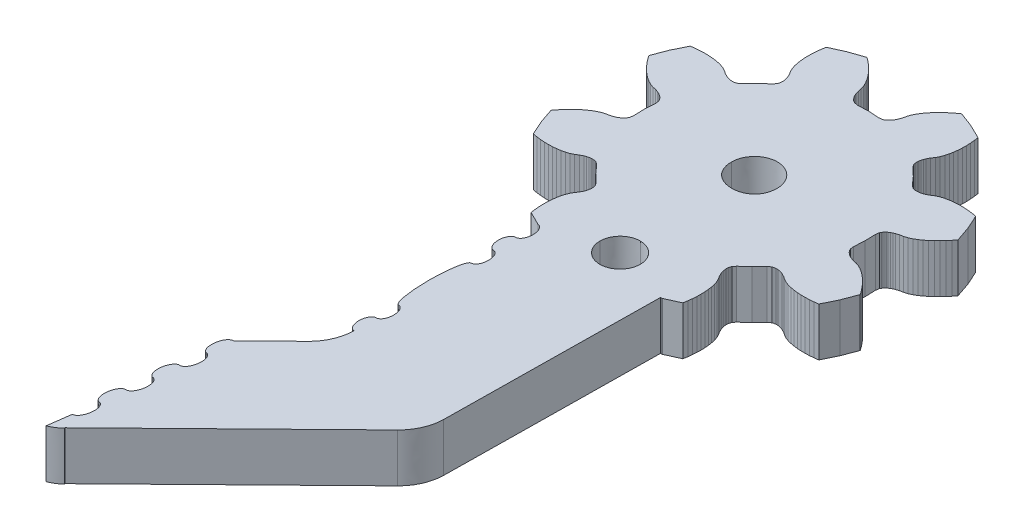
SolidWorks part; units mm, degrees
material "Acrylic (Medium-high impact)"
ref_plane "Front Plane" through (0, 0, 0) normal (0, 0, 1) x (1, 0, 0)
ref_plane "Top Plane" through (0, 0, 0) normal (0, 1, 0) x (1, 0, 0)
ref_plane "Right Plane" through (0, 0, 0) normal (1, 0, 0) x (0, 0, -1)
sketch "Sketch1" plane through (0, 0, 0) normal (0, 1, 0) x (1, 0, 0)
  line L63 (2.643, 3.6562) -> (2.7397, 3.6562)
  line L64 (2.7397, 3.6562) -> (3.6794, 4.0822)
  line L65 (3.6794, 4.0822) -> (3.726, 4.3637)
  line L66 (3.726, 4.3637) -> (3.7589, 4.641)
  line L67 (3.7589, 4.641) -> (3.7785, 4.9133)
  line L68 (3.7785, 4.9133) -> (3.7841, 5.1802)
  line L69 (3.7841, 5.1802) -> (3.7758, 5.441)
  line L70 (3.7758, 5.441) -> (3.7532, 5.6947)
  line L71 (3.7532, 5.6947) -> (3.7153, 5.9407)
  line L72 (3.7153, 5.9407) -> (3.6615, 6.1772)
  line L73 (3.6615, 6.1772) -> (3.5887, 6.4021)
  line L74 (3.5887, 6.4021) -> (3.487, 6.608)
  line L75 (3.487, 6.608) -> (3.364, 6.8)
  line L76 (3.364, 6.8) -> (3.2631, 7.0068)
  line L77 (3.2631, 7.0068) -> (3.2231, 7.1171)
  line L78 (3.2231, 7.1171) -> (3.1915, 7.2338)
  line L79 (3.1915, 7.2338) -> (3.1713, 7.358)
  line L80 (3.1713, 7.358) -> (3.1666, 7.4245)
  line L81 (3.1666, 7.4245) -> (3.1667, 7.4943)
  line L82 (3.1667, 7.4943) -> (3.1734, 7.5693)
  line L83 (3.1734, 7.5693) -> (3.1901, 7.652)
  line L84 (3.1901, 7.652) -> (3.2251, 7.7489)
  line L85 (3.2251, 7.7489) -> (3.3642, 7.9288)
  line L86 (3.3642, 7.9288) -> (3.893, 8.3951)
  line L87 (3.893, 8.3951) -> (4.3749, 8.91)
  line L88 (4.3749, 8.91) -> (4.5589, 9.0437)
  line L89 (4.5589, 9.0437) -> (4.6567, 9.0755)
  line L90 (4.6567, 9.0755) -> (4.7396, 9.0896)
  line L91 (4.7396, 9.0896) -> (4.8146, 9.0942)
  line L92 (4.8146, 9.0942) -> (4.8843, 9.0922)
  line L93 (4.8843, 9.0922) -> (4.9504, 9.0853)
  line L94 (4.9504, 9.0853) -> (5.0739, 9.0611)
  line L95 (5.0739, 9.0611) -> (5.1891, 9.0259)
  line L96 (5.1891, 9.0259) -> (5.2981, 8.9822)
  line L97 (5.2981, 8.9822) -> (5.5012, 8.8748)
  line L98 (5.5012, 8.8748) -> (5.6889, 8.7458)
  line L99 (5.6889, 8.7458) -> (5.8911, 8.6373)
  line L100 (5.8911, 8.6373) -> (6.1133, 8.5575)
  line L101 (6.1133, 8.5575) -> (6.3474, 8.496)
  line L102 (6.3474, 8.496) -> (6.5916, 8.4505)
  line L103 (6.5916, 8.4505) -> (6.8442, 8.4198)
  line L104 (6.8442, 8.4198) -> (7.1039, 8.4033)
  line L105 (7.1039, 8.4033) -> (7.3705, 8.4005)
  line L106 (7.3705, 8.4005) -> (7.6428, 8.4114)
  line L107 (7.6428, 8.4114) -> (7.9205, 8.4357)
  line L108 (7.9205, 8.4357) -> (8.2028, 8.4735)
  line L109 (8.2028, 8.4735) -> (8.6574, 9.4011)
  line L110 (8.6574, 9.4011) -> (9.0212, 10.3682)
  line L111 (9.0212, 10.3682) -> (8.8555, 10.6002)
  line L112 (8.8555, 10.6002) -> (8.6831, 10.8195)
  line L113 (8.6831, 10.8195) -> (8.5045, 11.0258)
  line L114 (8.5045, 11.0258) -> (8.3202, 11.2187)
  line L115 (8.3202, 11.2187) -> (8.1302, 11.3972)
  line L116 (8.1302, 11.3972) -> (7.935, 11.5605)
  line L117 (7.935, 11.5605) -> (7.7348, 11.7077)
  line L118 (7.7348, 11.7077) -> (7.5298, 11.8366)
  line L119 (7.5298, 11.8366) -> (7.3196, 11.9442)
  line L120 (7.3196, 11.9442) -> (7.1023, 12.0177)
  line L121 (7.1023, 12.0177) -> (6.8799, 12.0665)
  line L122 (6.8799, 12.0665) -> (6.6625, 12.1413)
  line L123 (6.6625, 12.1413) -> (6.5562, 12.1908)
  line L124 (6.5562, 12.1908) -> (6.4518, 12.2509)
  line L125 (6.4518, 12.2509) -> (6.3494, 12.3245)
  line L126 (6.3494, 12.3245) -> (6.2995, 12.3681)
  line L127 (6.2995, 12.3681) -> (6.2502, 12.4176)
  line L128 (6.2502, 12.4176) -> (6.202, 12.4756)
  line L129 (6.202, 12.4756) -> (6.1556, 12.5459)
  line L130 (6.1556, 12.5459) -> (6.1118, 12.6389)
  line L131 (6.1118, 12.6389) -> (6.0832, 12.8648)
  line L132 (6.0832, 12.8648) -> (6.1279, 13.5692)
  line L133 (6.1279, 13.5692) -> (6.1053, 14.2746)
  line L134 (6.1053, 14.2746) -> (6.141, 14.4995)
  line L135 (6.141, 14.4995) -> (6.1877, 14.5911)
  line L136 (6.1877, 14.5911) -> (6.2364, 14.6599)
  line L137 (6.2364, 14.6599) -> (6.2862, 14.7161)
  line L138 (6.2862, 14.7161) -> (6.337, 14.7642)
  line L139 (6.337, 14.7642) -> (6.3884, 14.8063)
  line L140 (6.3884, 14.8063) -> (6.4928, 14.8765)
  line L141 (6.4928, 14.8765) -> (6.5992, 14.9333)
  line L142 (6.5992, 14.9333) -> (6.7071, 14.9796)
  line L143 (6.7071, 14.9796) -> (6.9266, 15.0474)
  line L144 (6.9266, 15.0474) -> (7.1505, 15.0891)
  line L145 (7.1505, 15.0891) -> (7.3699, 15.1557)
  line L146 (7.3699, 15.1557) -> (7.5834, 15.2566)
  line L147 (7.5834, 15.2566) -> (7.7925, 15.3791)
  line L148 (7.7925, 15.3791) -> (7.9971, 15.5199)
  line L149 (7.9971, 15.5199) -> (8.1974, 15.6771)
  line L150 (8.1974, 15.6771) -> (8.3926, 15.8495)
  line L151 (8.3926, 15.8495) -> (8.583, 16.0364)
  line L152 (8.583, 16.0364) -> (8.768, 16.2371)
  line L153 (8.768, 16.2371) -> (8.9471, 16.4508)
  line L154 (8.9471, 16.4508) -> (9.1201, 16.6774)
  line L155 (9.1201, 16.6774) -> (8.7867, 17.6555)
  line L156 (8.7867, 17.6555) -> (8.3615, 18.5971)
  line L157 (8.3615, 18.5971) -> (8.0806, 18.6436)
  line L158 (8.0806, 18.6436) -> (7.8038, 18.6767)
  line L159 (7.8038, 18.6767) -> (7.5319, 18.6962)
  line L160 (7.5319, 18.6962) -> (7.2654, 18.7018)
  line L161 (7.2654, 18.7018) -> (7.0052, 18.6934)
  line L162 (7.0052, 18.6934) -> (6.7518, 18.6708)
  line L163 (6.7518, 18.6708) -> (6.5065, 18.633)
  line L164 (6.5065, 18.633) -> (6.2704, 18.579)
  line L165 (6.2704, 18.579) -> (6.0459, 18.5062)
  line L166 (6.0459, 18.5062) -> (5.8404, 18.4041)
  line L167 (5.8404, 18.4041) -> (5.6486, 18.2808)
  line L168 (5.6486, 18.2808) -> (5.4421, 18.18)
  line L169 (5.4421, 18.18) -> (5.332, 18.1397)
  line L170 (5.332, 18.1397) -> (5.2157, 18.1082)
  line L171 (5.2157, 18.1082) -> (5.0915, 18.0878)
  line L172 (5.0915, 18.0878) -> (5.0254, 18.0831)
  line L173 (5.0254, 18.0831) -> (4.9555, 18.0833)
  line L174 (4.9555, 18.0833) -> (4.8807, 18.0902)
  line L175 (4.8807, 18.0902) -> (4.7983, 18.1069)
  line L176 (4.7983, 18.1069) -> (4.7016, 18.1417)
  line L177 (4.7016, 18.1417) -> (4.5218, 18.2812)
  line L178 (4.5218, 18.2812) -> (4.0563, 18.811)
  line L179 (4.0563, 18.811) -> (3.5423, 19.2936)
  line L180 (3.5423, 19.2936) -> (3.4091, 19.4779)
  line L181 (3.4091, 19.4779) -> (3.3772, 19.5759)
  line L182 (3.3772, 19.5759) -> (3.3631, 19.659)
  line L183 (3.3631, 19.659) -> (3.3587, 19.7341)
  line L184 (3.3587, 19.7341) -> (3.3605, 19.8041)
  line L185 (3.3605, 19.8041) -> (3.3674, 19.8702)
  line L186 (3.3674, 19.8702) -> (3.3917, 19.9939)
  line L187 (3.3917, 19.9939) -> (3.4268, 20.1093)
  line L188 (3.4268, 20.1093) -> (3.4703, 20.2185)
  line L189 (3.4703, 20.2185) -> (3.5777, 20.4219)
  line L190 (3.5777, 20.4219) -> (3.7064, 20.61)
  line L191 (3.7064, 20.61) -> (3.8147, 20.8127)
  line L192 (3.8147, 20.8127) -> (3.8944, 21.0352)
  line L193 (3.8944, 21.0352) -> (3.9558, 21.2699)
  line L194 (3.9558, 21.2699) -> (4.0011, 21.5145)
  line L195 (4.0011, 21.5145) -> (4.0319, 21.7674)
  line L196 (4.0319, 21.7674) -> (4.0483, 22.0277)
  line L197 (4.0483, 22.0277) -> (4.0509, 22.2946)
  line L198 (4.0509, 22.2946) -> (4.04, 22.5675)
  line L199 (4.04, 22.5675) -> (4.0158, 22.8456)
  line L200 (4.0158, 22.8456) -> (3.9782, 23.1285)
  line L201 (3.9782, 23.1285) -> (3.0521, 23.5839)
  line L202 (3.0521, 23.5839) -> (2.0868, 23.9484)
  line L203 (2.0868, 23.9484) -> (1.8554, 23.7823)
  line L204 (1.8554, 23.7823) -> (1.6364, 23.6097)
  line L205 (1.6364, 23.6097) -> (1.4304, 23.4308)
  line L206 (1.4304, 23.4308) -> (1.238, 23.2461)
  line L207 (1.238, 23.2461) -> (1.0598, 23.0557)
  line L208 (1.0598, 23.0557) -> (0.8966, 22.8604)
  line L209 (0.8966, 22.8604) -> (0.7498, 22.6598)
  line L210 (0.7498, 22.6598) -> (0.621, 22.4543)
  line L211 (0.621, 22.4543) -> (0.5138, 22.2438)
  line L212 (0.5138, 22.2438) -> (0.4403, 22.0259)
  line L213 (0.4403, 22.0259) -> (0.3917, 21.8031)
  line L214 (0.3917, 21.8031) -> (0.3171, 21.5856)
  line L215 (0.3171, 21.5856) -> (0.2677, 21.4791)
  line L216 (0.2677, 21.4791) -> (0.2075, 21.3742)
  line L217 (0.2075, 21.3742) -> (0.1342, 21.2719)
  line L218 (0.1342, 21.2719) -> (0.0906, 21.2217)
  line L219 (0.0906, 21.2217) -> (0.0411, 21.1725)
  line L220 (0.0411, 21.1725) -> (-0.0167, 21.1242)
  line L221 (-0.0167, 21.1242) -> (-0.0867, 21.0776)
  line L222 (-0.0867, 21.0776) -> (-0.1798, 21.0339)
  line L223 (-0.1798, 21.0339) -> (-0.4053, 21.005)
  line L224 (-0.4053, 21.005) -> (-1.1084, 21.05)
  line L225 (-1.1084, 21.05) -> (-1.8125, 21.0272)
  line L226 (-1.8125, 21.0272) -> (-2.0369, 21.0631)
  line L227 (-2.0369, 21.0631) -> (-2.1285, 21.1097)
  line L228 (-2.1285, 21.1097) -> (-2.1971, 21.1585)
  line L229 (-2.1971, 21.1585) -> (-2.2533, 21.2086)
  line L230 (-2.2533, 21.2086) -> (-2.3012, 21.2594)
  line L231 (-2.3012, 21.2594) -> (-2.3431, 21.3109)
  line L232 (-2.3431, 21.3109) -> (-2.4134, 21.4156)
  line L233 (-2.4134, 21.4156) -> (-2.47, 21.5221)
  line L234 (-2.47, 21.5221) -> (-2.5162, 21.6301)
  line L235 (-2.5162, 21.6301) -> (-2.584, 21.8499)
  line L236 (-2.584, 21.8499) -> (-2.6254, 22.0742)
  line L237 (-2.6254, 22.0742) -> (-2.692, 22.2941)
  line L238 (-2.692, 22.2941) -> (-2.7928, 22.508)
  line L239 (-2.7928, 22.508) -> (-2.915, 22.7174)
  line L240 (-2.915, 22.7174) -> (-3.0554, 22.9224)
  line L241 (-3.0554, 22.9224) -> (-3.2124, 23.123)
  line L242 (-3.2124, 23.123) -> (-3.3846, 23.3188)
  line L243 (-3.3846, 23.3188) -> (-3.571, 23.5095)
  line L244 (-3.571, 23.5095) -> (-3.7713, 23.6947)
  line L245 (-3.7713, 23.6947) -> (-3.9848, 23.8743)
  line L246 (-3.9848, 23.8743) -> (-4.211, 24.0474)
  line L247 (-4.211, 24.0474) -> (-5.1873, 23.7136)
  line L248 (-5.1873, 23.7136) -> (-6.1272, 23.2876)
  line L249 (-6.1272, 23.2876) -> (-6.1736, 23.006)
  line L250 (-6.1736, 23.006) -> (-6.2067, 22.7288)
  line L251 (-6.2067, 22.7288) -> (-6.2259, 22.4565)
  line L252 (-6.2259, 22.4565) -> (-6.2315, 22.1894)
  line L253 (-6.2315, 22.1894) -> (-6.2234, 21.9287)
  line L254 (-6.2234, 21.9287) -> (-6.2006, 21.6749)
  line L255 (-6.2006, 21.6749) -> (-6.1631, 21.429)
  line L256 (-6.1631, 21.429) -> (-6.1089, 21.1926)
  line L257 (-6.1089, 21.1926) -> (-6.0363, 20.9677)
  line L258 (-6.0363, 20.9677) -> (-5.9343, 20.7617)
  line L259 (-5.9343, 20.7617) -> (-5.8115, 20.5698)
  line L260 (-5.8115, 20.5698) -> (-5.7107, 20.363)
  line L261 (-5.7107, 20.363) -> (-5.6707, 20.2526)
  line L262 (-5.6707, 20.2526) -> (-5.639, 20.136)
  line L263 (-5.639, 20.136) -> (-5.6188, 20.0115)
  line L264 (-5.6188, 20.0115) -> (-5.6141, 19.9453)
  line L265 (-5.6141, 19.9453) -> (-5.6143, 19.8755)
  line L266 (-5.6143, 19.8755) -> (-5.621, 19.8003)
  line L267 (-5.621, 19.8003) -> (-5.6377, 19.7178)
  line L268 (-5.6377, 19.7178) -> (-5.6727, 19.6209)
  line L269 (-5.6727, 19.6209) -> (-5.8117, 19.4409)
  line L270 (-5.8117, 19.4409) -> (-6.3405, 18.9745)
  line L271 (-6.3405, 18.9745) -> (-6.8224, 18.4597)
  line L272 (-6.8224, 18.4597) -> (-7.0064, 18.326)
  line L273 (-7.0064, 18.326) -> (-7.1041, 18.2943)
  line L274 (-7.1041, 18.2943) -> (-7.187, 18.2801)
  line L275 (-7.187, 18.2801) -> (-7.2622, 18.2756)
  line L276 (-7.2622, 18.2756) -> (-7.3319, 18.2776)
  line L277 (-7.3319, 18.2776) -> (-7.398, 18.2843)
  line L278 (-7.398, 18.2843) -> (-7.5215, 18.3086)
  line L279 (-7.5215, 18.3086) -> (-7.6367, 18.3438)
  line L280 (-7.6367, 18.3438) -> (-7.7455, 18.3875)
  line L281 (-7.7455, 18.3875) -> (-7.9487, 18.4949)
  line L282 (-7.9487, 18.4949) -> (-8.1364, 18.624)
  line L283 (-8.1364, 18.624) -> (-8.3388, 18.7325)
  line L284 (-8.3388, 18.7325) -> (-8.5609, 18.8123)
  line L285 (-8.5609, 18.8123) -> (-8.795, 18.8738)
  line L286 (-8.795, 18.8738) -> (-9.0391, 18.9193)
  line L287 (-9.0391, 18.9193) -> (-9.2916, 18.9499)
  line L288 (-9.2916, 18.9499) -> (-9.5516, 18.9665)
  line L289 (-9.5516, 18.9665) -> (-9.8181, 18.9692)
  line L290 (-9.8181, 18.9692) -> (-10.0904, 18.9583)
  line L291 (-10.0904, 18.9583) -> (-10.3681, 18.934)
  line L292 (-10.3681, 18.934) -> (-10.6504, 18.8963)
  line L293 (-10.6504, 18.8963) -> (-11.105, 17.9686)
  line L294 (-11.105, 17.9686) -> (-11.4688, 17.0016)
  line L295 (-11.4688, 17.0016) -> (-11.3029, 16.7696)
  line L296 (-11.3029, 16.7696) -> (-11.1307, 16.5502)
  line L297 (-11.1307, 16.5502) -> (-10.9521, 16.3439)
  line L298 (-10.9521, 16.3439) -> (-10.7676, 16.151)
  line L299 (-10.7676, 16.151) -> (-10.5778, 15.9725)
  line L300 (-10.5778, 15.9725) -> (-10.3826, 15.8091)
  line L301 (-10.3826, 15.8091) -> (-10.1824, 15.6619)
  line L302 (-10.1824, 15.6619) -> (-9.9773, 15.5331)
  line L303 (-9.9773, 15.5331) -> (-9.7672, 15.4255)
  line L304 (-9.7672, 15.4255) -> (-9.5499, 15.3521)
  line L305 (-9.5499, 15.3521) -> (-9.3275, 15.3032)
  line L306 (-9.3275, 15.3032) -> (-9.1101, 15.2285)
  line L307 (-9.1101, 15.2285) -> (-9.0039, 15.1789)
  line L308 (-9.0039, 15.1789) -> (-8.8993, 15.1187)
  line L309 (-8.8993, 15.1187) -> (-8.797, 15.0452)
  line L310 (-8.797, 15.0452) -> (-8.747, 15.0017)
  line L311 (-8.747, 15.0017) -> (-8.6978, 14.952)
  line L312 (-8.6978, 14.952) -> (-8.6498, 14.8941)
  line L313 (-8.6498, 14.8941) -> (-8.6032, 14.8239)
  line L314 (-8.6032, 14.8239) -> (-8.5594, 14.7308)
  line L315 (-8.5594, 14.7308) -> (-8.5306, 14.505)
  line L316 (-8.5306, 14.505) -> (-8.5755, 13.8005)
  line L317 (-8.5755, 13.8005) -> (-8.5529, 13.0951)
  line L318 (-8.5529, 13.0951) -> (-8.5886, 12.8702)
  line L319 (-8.5886, 12.8702) -> (-8.6353, 12.7784)
  line L320 (-8.6353, 12.7784) -> (-8.684, 12.7099)
  line L321 (-8.684, 12.7099) -> (-8.7338, 12.6534)
  line L322 (-8.7338, 12.6534) -> (-8.7845, 12.6056)
  line L323 (-8.7845, 12.6056) -> (-8.836, 12.5635)
  line L324 (-8.836, 12.5635) -> (-8.9404, 12.4932)
  line L325 (-8.9404, 12.4932) -> (-9.0467, 12.4365)
  line L326 (-9.0467, 12.4365) -> (-9.1547, 12.3902)
  line L327 (-9.1547, 12.3902) -> (-9.3742, 12.3222)
  line L328 (-9.3742, 12.3222) -> (-9.5978, 12.2806)
  line L329 (-9.5978, 12.2806) -> (-9.8175, 12.2139)
  line L330 (-9.8175, 12.2139) -> (-10.0309, 12.1131)
  line L331 (-10.0309, 12.1131) -> (-10.24, 11.9905)
  line L332 (-10.24, 11.9905) -> (-10.4447, 11.8499)
  line L333 (-10.4447, 11.8499) -> (-10.6448, 11.6926)
  line L334 (-10.6448, 11.6926) -> (-10.8404, 11.5203)
  line L335 (-10.8404, 11.5203) -> (-11.0307, 11.3334)
  line L336 (-11.0307, 11.3334) -> (-11.2156, 11.1327)
  line L337 (-11.2156, 11.1327) -> (-11.3948, 10.9188)
  line L338 (-11.3948, 10.9188) -> (-11.5677, 10.6922)
  line L339 (-11.5677, 10.6922) -> (-11.2345, 9.7141)
  line L340 (-11.2345, 9.7141) -> (-10.809, 8.7727)
  line L341 (-10.809, 8.7727) -> (-10.5282, 8.726)
  line L342 (-10.5282, 8.726) -> (-10.2513, 8.693)
  line L343 (-10.2513, 8.693) -> (-9.9794, 8.6736)
  line L344 (-9.9794, 8.6736) -> (-9.713, 8.668)
  line L345 (-9.713, 8.668) -> (-9.4528, 8.6763)
  line L346 (-9.4528, 8.6763) -> (-9.1994, 8.699)
  line L347 (-9.1994, 8.699) -> (-8.954, 8.7368)
  line L348 (-8.954, 8.7368) -> (-8.718, 8.7908)
  line L349 (-8.718, 8.7908) -> (-8.4935, 8.8636)
  line L350 (-8.4935, 8.8636) -> (-8.2877, 8.9657)
  line L351 (-8.2877, 8.9657) -> (-8.0963, 9.0887)
  line L352 (-8.0963, 9.0887) -> (-7.8899, 9.1898)
  line L353 (-7.8899, 9.1898) -> (-7.7796, 9.23)
  line L354 (-7.7796, 9.23) -> (-7.6633, 9.2616)
  line L355 (-7.6633, 9.2616) -> (-7.5391, 9.282)
  line L356 (-7.5391, 9.282) -> (-7.4728, 9.2867)
  line L357 (-7.4728, 9.2867) -> (-7.4031, 9.2863)
  line L358 (-7.4031, 9.2863) -> (-7.3283, 9.2796)
  line L359 (-7.3283, 9.2796) -> (-7.2457, 9.2629)
  line L360 (-7.2457, 9.2629) -> (-7.1492, 9.2281)
  line L361 (-7.1492, 9.2281) -> (-6.9693, 9.0885)
  line L362 (-6.9693, 9.0885) -> (-6.5039, 8.5588)
  line L363 (-6.5039, 8.5588) -> (-5.9899, 8.076)
  line L364 (-5.9899, 8.076) -> (-5.8565, 7.8916)
  line L365 (-5.8565, 7.8916) -> (-5.8248, 7.7938)
  line L366 (-5.8248, 7.7938) -> (-5.8106, 7.7108)
  line L367 (-5.8106, 7.7108) -> (-5.8063, 7.6356)
  line L368 (-5.8063, 7.6356) -> (-5.8081, 7.5656)
  line L369 (-5.8081, 7.5656) -> (-5.815, 7.4996)
  line L370 (-5.815, 7.4996) -> (-5.8393, 7.3758)
  line L371 (-5.8393, 7.3758) -> (-5.8744, 7.2602)
  line L372 (-5.8744, 7.2602) -> (-5.9179, 7.1512)
  line L373 (-5.9179, 7.1512) -> (-6.025, 6.9478)
  line L374 (-6.025, 6.9478) -> (-6.154, 6.7597)
  line L375 (-6.154, 6.7597) -> (-6.2623, 6.557)
  line L376 (-6.2623, 6.557) -> (-6.342, 6.3346)
  line L377 (-6.342, 6.3346) -> (-6.4034, 6.0998)
  line L378 (-6.4034, 6.0998) -> (-6.4487, 5.8553)
  line L379 (-6.4487, 5.8553) -> (-6.4793, 5.6023)
  line L380 (-6.4793, 5.6023) -> (-6.4958, 5.342)
  line L381 (-6.4958, 5.342) -> (-6.4985, 5.0749)
  line L382 (-6.4985, 5.0749) -> (-6.4878, 4.8023)
  line L383 (-6.4878, 4.8023) -> (-6.4633, 4.5239)
  line L384 (-6.4633, 4.5239) -> (-6.4258, 4.2413)
  line L385 (-6.4258, 4.2413) -> (-5.4997, 3.7857)
  line L386 (-5.4997, 3.7857) -> (-5.5129, 3.7857)
  line L387 (-6.4164, -10.3805) -> (-8.8908, -12.7984)
  line L388 (-9.9992, -22.2342) -> (-10.2013, -23.7388)
  line L389 (-10.2013, -23.7388) -> (-10.2286, -23.7385)
  line L390 (-9.4566, -23.2889) -> (-9.4704, -23.2428)
  line L391 (-9.4704, -23.2428) -> (1.5439, -12.4802)
  line L392 (1.5439, -12.4802) -> (1.5454, -12.4767)
  line L393 (2.461, -10.3716) -> (2.643, 3.6562)
  spline S3 degree 3 poles (-2.7211, 13.6747) (-2.7211, 11.6883) (0.2737, 11.6883) (0.2737, 13.6745) knots 2 2 2 2 3 3 3 3
  spline S4 degree 3 poles (0.2737, 13.6745) (0.2737, 14.5086) (-0.397, 15.1848) (-1.2237, 15.1848) (-2.0508, 15.1848) (-2.7211, 14.5086) (-2.7211, 13.6747) knots 0 0 0 0 1 1 1 2 2 2 2
  spline S5 degree 3 poles (-2.5461, 4.8915) (-2.5551, 4.1598) (-1.9706, 3.5593) (-1.2402, 3.55) knots 3 3 3 3 4 4 4 4
  spline S6 degree 3 poles (-1.2072, 6.1998) (-1.9378, 6.209) (-2.537, 5.6231) (-2.5461, 4.8915) knots 2 2 2 2 3 3 3 3
  spline S7 degree 3 poles (0.0987, 4.8583) (0.1077, 5.5902) (-0.4768, 6.1907) (-1.2072, 6.1998) knots 1 1 1 1 2 2 2 2
  spline S8 degree 3 poles (-1.2402, 3.55) (-0.51, 3.5409) (0.0897, 4.1268) (0.0987, 4.8583) knots 0 0 0 0 1 1 1 1
  spline S9 degree 3 poles (-5.5129, 3.7857) (-5.2851, 3.7826) (-5.1005, 3.4533) (-5.1005, 3.0504) knots 324 324 324 324 325 325 325 325
  spline S10 degree 3 poles (-5.1005, 3.0504) (-5.1005, 2.6472) (-5.2851, 2.3234) (-5.5129, 2.3265) knots 325 325 325 325 326 326 326 326
  spline S11 degree 3 poles (-5.5129, 2.3265) (-5.7406, 2.3295) (-5.9251, 2.0055) (-5.9251, 1.6026) knots 326 326 326 326 327 327 327 327
  spline S12 degree 3 poles (-5.9251, 1.6026) (-5.9251, 1.1996) (-5.7406, 0.8703) (-5.5129, 0.867) knots 327 327 327 327 328 328 328 328
  spline S13 degree 3 poles (-5.5129, 0.867) (-5.2851, 0.8638) (-5.1005, 0.5347) (-5.1005, 0.1317) knots 328 328 328 328 329 329 329 329
  spline S14 degree 3 poles (-5.1005, 0.1317) (-5.1005, -0.2712) (-5.2851, -0.5955) (-5.5129, -0.5924) knots 329 329 329 329 330 330 330 330
  spline S15 degree 3 poles (-5.5129, -0.5924) (-5.7408, -0.582) (-5.9253, -1.6391) (-5.9253, -2.9531) knots 330 330 330 330 331 331 331 331
  spline S16 degree 3 poles (-5.9253, -2.9531) (-5.9253, -4.2674) (-5.7408, -5.3411) (-5.5129, -5.3516) knots 331 331 331 331 332 332 332 332
  spline S17 degree 3 poles (-5.5129, -5.3516) (-5.2853, -5.3549) (-5.1007, -5.684) (-5.1007, -6.0872) knots 332 332 332 332 333 333 333 333
  spline S18 degree 3 poles (-5.1007, -6.0872) (-5.1007, -6.49) (-5.2853, -6.8141) (-5.5129, -6.8109) knots 333 333 333 333 334 334 334 334
  spline S19 degree 3 poles (-5.5129, -6.8109) (-5.7408, -6.8078) (-5.9253, -7.1319) (-5.9253, -7.5348) knots 334 334 334 334 335 335 335 335
  spline S20 degree 3 poles (-5.9253, -7.5348) (-5.9253, -7.9377) (-5.7408, -8.267) (-5.5129, -8.2701) knots 335 335 335 335 336 336 336 336
  spline S21 degree 3 poles (-5.5129, -8.2701) (-5.5229, -9.0659) (-5.848, -9.825) (-6.4164, -10.3805) knots 336 336 336 336 337 337 337 337
  spline S22 degree 3 poles (-8.8908, -12.7984) (-9.1174, -12.7752) (-9.3424, -13.1085) (-9.3934, -13.5427) knots 338 338 338 338 339 339 339 339
  spline S23 degree 3 poles (-9.3934, -13.5427) (-9.4444, -13.977) (-9.3021, -14.3478) (-9.0756, -14.3711) knots 339 339 339 339 340 340 340 340
  spline S24 degree 3 poles (-9.0756, -14.3711) (-8.849, -14.3943) (-8.7068, -14.7651) (-8.7577, -15.1993) knots 340 340 340 340 341 341 341 341
  spline S25 degree 3 poles (-8.7577, -15.1993) (-8.8088, -15.6336) (-9.0339, -15.9669) (-9.2603, -15.9437) knots 341 341 341 341 342 342 342 342
  spline S26 degree 3 poles (-9.2603, -15.9437) (-9.4869, -15.9205) (-9.7118, -16.2538) (-9.7629, -16.6879) knots 342 342 342 342 343 343 343 343
  spline S27 degree 3 poles (-9.7629, -16.6879) (-9.8139, -17.1222) (-9.6716, -17.4931) (-9.445, -17.5163) knots 343 343 343 343 344 344 344 344
  spline S28 degree 3 poles (-9.445, -17.5163) (-9.2185, -17.5395) (-9.0763, -17.9104) (-9.1272, -18.3445) knots 344 344 344 344 345 345 345 345
  spline S29 degree 3 poles (-9.1272, -18.3445) (-9.1782, -18.7789) (-9.4034, -19.1122) (-9.6297, -19.089) knots 345 345 345 345 346 346 346 346
  spline S30 degree 3 poles (-9.6297, -19.089) (-9.8563, -19.0657) (-10.0812, -19.399) (-10.1323, -19.8334) knots 346 346 346 346 347 347 347 347
  spline S31 degree 3 poles (-10.1323, -19.8334) (-10.1834, -20.2675) (-10.041, -20.6384) (-9.8144, -20.6616) knots 347 347 347 347 348 348 348 348
  spline S32 degree 3 poles (-9.8144, -20.6616) (-9.5879, -20.6849) (-9.4455, -21.0557) (-9.4966, -21.49) knots 348 348 348 348 349 349 349 349
  spline S33 degree 3 poles (-9.4966, -21.49) (-9.5477, -21.9242) (-9.7726, -22.2574) (-9.9992, -22.2342) knots 349 349 349 349 350 350 350 350
  spline S34 degree 3 poles (-10.2286, -23.7385) (-10.2294, -23.8056) (-9.6947, -23.5215) (-9.4566, -23.2889) knots 352 352 352 352 353 353 353 353
  spline S35 degree 3 poles (1.5454, -12.4767) (2.1172, -11.9245) (2.4465, -11.1672) (2.461, -10.3716) knots 356 356 356 356 357 357 357 357
extrude "Boss-Extrude1" add sketch "Sketch1" along normal blind 3.175
